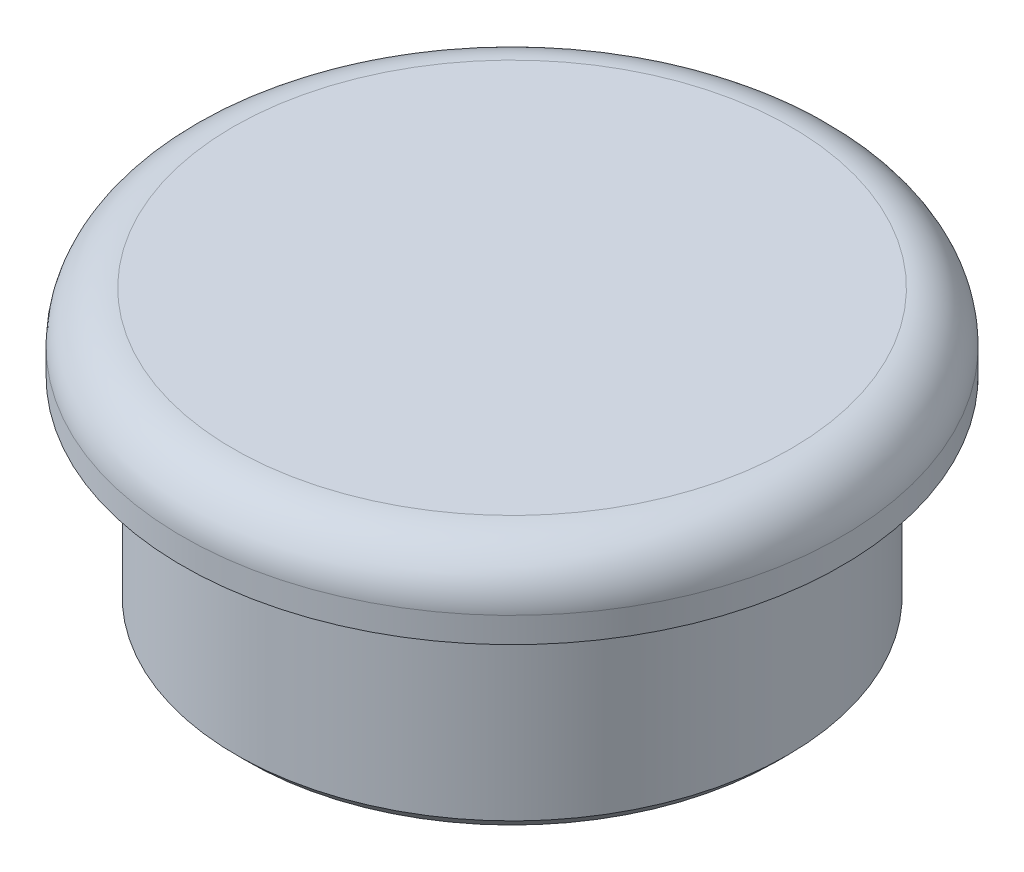
SolidWorks part; units mm, degrees
ref_plane "Front Plane" through (0, 0, 0) normal (0, 0, 1) x (1, 0, 0)
ref_plane "Top Plane" through (0, 0, 0) normal (0, 1, 0) x (1, 0, 0)
ref_plane "Right Plane" through (0, 0, 0) normal (1, 0, 0) x (0, 0, -1)
sketch "Sketch3" plane through (0, 0, 0) normal (0, 0, 1) x (1, 0, 0)
  line L0 (-34.629, 22.5434) -> (-13.9915, 22.5434)
  line L1 (-13.9915, 22.5434) -> (-13.9915, 17.7809)
  line L2 (-13.9915, 17.7809) -> (-28.9775, 17.7809)
  line L3 (-28.9775, 17.7809) -> (-28.9775, 5.0809)
  line L4 (-28.9775, 5.0809) -> (-31.2635, 5.0809)
  line L5 (-31.2635, 5.0809) -> (-31.2635, 17.7809)
  line L6 (-31.2635, 17.7809) -> (-34.629, 17.7809)
  line L7 (-34.629, 17.7809) -> (-34.629, 22.5434)
  dimension "D1" = 20.6375
  dimension "D2" = 17.4625
  dimension "D3" = 12.7
  dimension "D4" = 14.986
  dimension "D5" = 17.272
  dimension "D6" = 4.7625
revolve "Revolve1" add sketch "Sketch3" angle 360 about L1
fillet "Fillet1" radius 3.175 1 edges at (-34.629, 22.5434, 0)
chamfer "Chamfer1" distance 0.762 angle 45 2 edges at (-31.2635, 17.7809, 0) (-31.2635, 5.0809, 0)
fillet "Fillet2" radius 2.54 1 edges at (-28.9775, 17.7809, 0)
